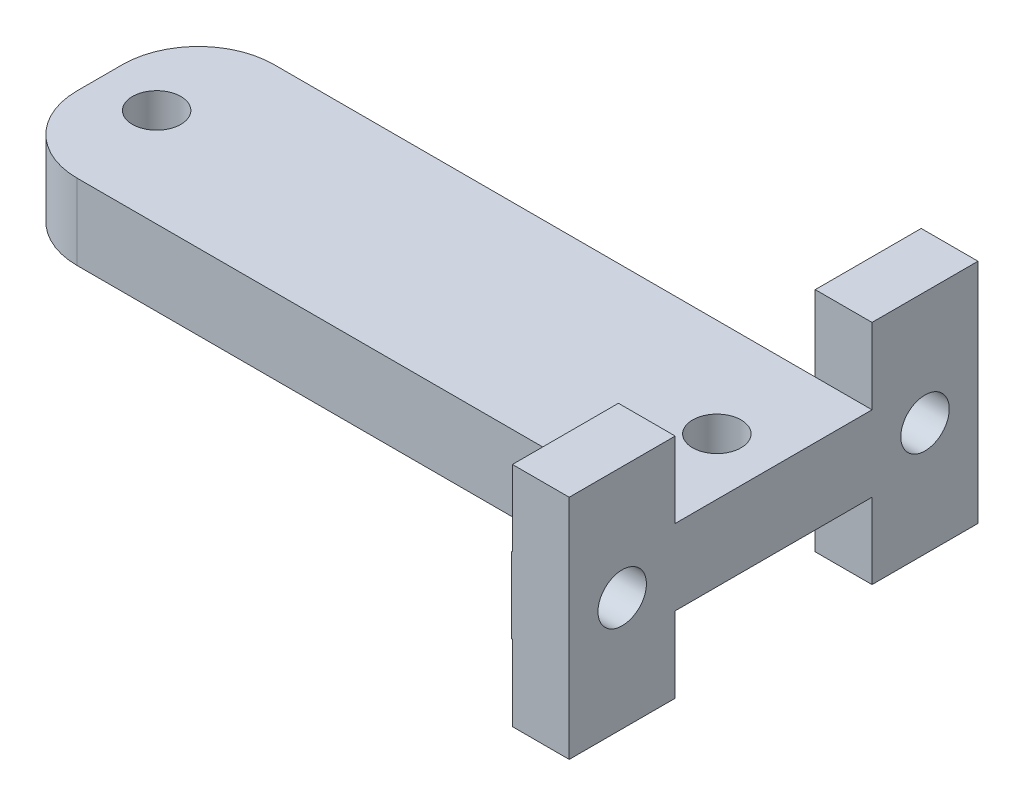
SolidWorks part; units mm, degrees
ref_plane "前视基准面" through (0, 0, 0) normal (0, 0, 1) x (1, 0, 0)
ref_plane "上视基准面" through (0, 0, 0) normal (0, 1, 0) x (1, 0, 0)
ref_plane "右视基准面" through (0, 0, 0) normal (1, 0, 0) x (0, 0, -1)
sketch "草图1" plane through (0, 0, 0) normal (0, 1, 0) x (1, 0, 0)
  line L0 (0, 0) -> (0, -100)
  line L1 (0, 0) -> (100, 0)
  line L2 (100, 0) -> (100, -100)
  line L3 (100, -100) -> (0, -100)
  dimension "D1" = 100
extrude "凸台-拉伸1" add sketch "草图1" along normal blind 10
sketch "草图2" plane through (0, 10, 0) normal (0, 1, 0) x (1, 0, 0)
  line L0 (20.6546, -10.25) -> (20.6546, -13)
  line L1 (20.6546, -13) -> (50.1546, -13)
  line L2 (50.1546, -13) -> (50.1546, -10.25)
  line L3 (50.1546, -10.25) -> (53.9046, -10.25)
  line L4 (16.9046, -2.75) -> (20.6546, -2.75)
  line L5 (20.6546, -2.75) -> (20.6546, 0)
  line L6 (100, 0) -> (0, 0) construction
  line L7 (20.6546, 0) -> (20.6546, -2.75) construction
  line L8 (20.6546, 0) -> (50, 0)
  line L9 (50, 0) -> (50.1546, -2.75)
  line L10 (50.1546, -2.75) -> (53.9046, -2.75)
  line L11 (16.9046, -10.25) -> (20.6546, -10.25)
  line L12 (20.6546, 0) -> (0, 0)
  line L13 (0, 0) -> (0, -100)
  line L14 (0, -100) -> (100, -100)
  line L15 (100, -100) -> (100, 0)
  line L16 (100, 0) -> (50, 0)
  line L17 (20.6546, -13) -> (0, -13)
  line L18 (50.1546, -13) -> (100, -13)
  line L19 (100, -13) -> (100, -100)
  arc A0 (53.9046, -10.25) -> (53.9046, -2.75) centre (53.9046, -6.5) ccw
  arc A1 (16.9046, -2.75) -> (16.9046, -10.25) centre (16.9046, -6.5) ccw
  line M3 (0, -100) -> (100, -100)
  line M4 (100, -100) -> (100, 0)
extrude "切除-拉伸3" cut sketch "草图2" against normal blind 27 contours L18 L1 L17 L13 M3 M4
sketch "草图4" plane through (0, 10, 0) normal (0, 1, 0) x (1, 0, 0)
  line L0 (16.9046, -6.5) -> (13.1546, -6.5)
  line L1 (13.1546, -6.5) -> (13.1546, 0)
  line L2 (100, 0) -> (0, 0) construction
  line L3 (13.1546, 0) -> (13.1546, -13)
  line L4 (0, -13) -> (100, -13) construction
  line L5 (53.9046, -6.5) -> (57.6546, -6.5)
  line L6 (57.6546, -6.5) -> (57.6546, -13)
  line L7 (57.6546, -13) -> (57.6546, 0)
  line L8 (57.6546, 0) -> (100, 0)
  line L9 (100, 0) -> (100, -13)
  line L10 (100, -13) -> (57.6546, -13)
  line L11 (13.1546, -13) -> (0, -13)
  line L12 (0, -13) -> (0, 0)
  line L13 (0, 0) -> (13.1546, 0)
  arc A0 (16.9046, -2.75) -> (16.9046, -10.25) centre (16.9046, -6.5) ccw construction
  arc A1 (53.9046, -10.25) -> (53.9046, -2.75) centre (53.9046, -6.5) ccw construction
  line M1 (0, -13) -> (100, -13)
  line M2 (100, -13) -> (100, 0)
  line M3 (100, 0) -> (0, 0)
  line M4 (0, 0) -> (0, -13)
extrude "切除-拉伸4" cut sketch "草图4" against normal blind 27 contours L3 L1 M3 M4 M1 | L7 L6 M1 M2 M3
sketch "草图5" plane through (0, 10, 0) normal (0, 1, 0) x (1, 0, 0)
  circle A0 centre (16.9046, -6.5) radius 1.6
  circle A1 centre (53.9046, -6.5) radius 1.6
extrude "切除-拉伸5" cut sketch "草图5" against normal blind 27
sketch "草图6" plane through (0, 0, 13) normal (0, 0, 1) x (1, 0, 0)
  line L0 (50.1546, 10) -> (50.1546, 0)
  line L1 (13.1546, 10) -> (57.6546, 10) construction
  line L2 (50.1546, 17.2) -> (50.1546, 10) construction
  line L3 (57.6546, 0) -> (13.1546, 0) construction
  line L4 (50.1546, 5) -> (13.1546, 5)
  line L5 (13.1546, 10) -> (13.1546, 0) construction
  line L6 (13.1546, 5) -> (13.1546, 0)
  line L7 (13.1546, 0) -> (50.1546, 0)
  line L8 (50.1546, 5) -> (57.6546, 5)
  line L9 (57.6546, 0) -> (57.6546, 10) construction
  line L10 (57.6546, 5) -> (57.6546, 0)
  line L11 (57.6546, 0) -> (50.1546, 0)
  line M2 (13.1546, 10) -> (13.1546, 0)
  line M3 (13.1546, 0) -> (57.6546, 0)
  line M4 (57.6546, 0) -> (57.6546, 10)
extrude "切除-拉伸6" cut sketch "草图6" against normal blind 27 contours L0 L4 M2 M3 | L8 L0 M3 M4
sketch "草图7" plane through (0, 10, 0) normal (0, 1, 0) x (1, 0, 0)
  line L0 (53.9046, -6.5) -> (53.9046, -13)
  line L1 (13.1546, -13) -> (57.6546, -13) construction
sketch "草图8" plane through (0, 0, 13) normal (0, 0, 1) x (1, 0, 0)
  line L0 (53.8487, 10) -> (53.8487, 5)
  line L1 (13.1546, 10) -> (57.6546, 10) construction
  line L2 (57.6546, 5) -> (13.1546, 5) construction
  line L3 (53.8487, 5) -> (57.6546, 5)
  line L4 (57.6546, 5) -> (57.6546, 10)
  line L5 (57.6546, 10) -> (53.8487, 10)
extrude "凸台-拉伸2" add sketch "草图8" along normal blind 7
sketch "草图9" plane through (0, 10, 0) normal (0, 1, 0) x (1, 0, 0)
  line L0 (53.9046, -6.5) -> (53.9046, 0)
  line L1 (57.6546, 0) -> (13.1546, 0) construction
sketch "草图10" plane through (0, 0, 0) normal (0, 0, -1) x (-1, 0, 0)
  line L0 (-53.9046, 10) -> (-53.9046, 5)
  line L1 (-57.6546, 5) -> (-13.1546, 5) construction
  line L2 (-53.9046, 5) -> (-57.6546, 5)
  line L3 (-57.6546, 5) -> (-57.6546, 10)
  line L4 (-57.6546, 10) -> (-53.9046, 10)
extrude "凸台-拉伸3" add sketch "草图10" along normal blind 7
sketch "草图11" plane through (13.1546, 0, 0) normal (-1, 0, 0) x (0, 0, 1)
  line L0 (6.5, 10) -> (6.5, 5)
  line L1 (6.5, 10) -> (13, 10) construction
  line L2 (6.5, 10) -> (0, 10) construction
  line L3 (0, 5) -> (13, 5) construction
fillet "圆角1" radius 5 1 edges at (13.1546, 7.5, 0)
fillet "圆角2" radius 5 1 edges at (13.1546, 7.5, 13)
sketch "草图14" plane through (57.6546, 0, 0) normal (1, 0, 0) x (0, 0, -1)
  line L0 (-13, 10) -> (-20, 10)
  line L1 (-20, 10) -> (-20, 15)
  line L2 (-20, 15) -> (-13, 15)
  line L3 (-13, 15) -> (-13, 10)
  line L4 (-20, 5) -> (-20, 0)
  line L5 (-20, 0) -> (-13, 0)
  line L6 (-13, 0) -> (-13, 5)
  line L7 (-13, 5) -> (-20, 5)
  line L8 (0, 10) -> (0, 15)
  line L9 (0, 10) -> (7, 10)
  line L10 (7, 10) -> (7, 15)
  line L11 (7, 15) -> (0, 15)
  line L12 (0, 5) -> (7, 5)
  line L13 (7, 5) -> (7, 0)
  line L14 (7, 0) -> (0, 0)
  line L15 (0, 0) -> (0, 5)
extrude "凸台-拉伸6" add sketch "草图14" against normal up to vertex (3.75 mm away) up to point (53.9046, 10, -7)
sketch "草图15" plane through (53.8487, 0, 0) normal (-1, 0, 0) x (0, 0, 1)
  line L0 (13, 10) -> (20, 5)
  line L1 (6.5, 10) -> (13, 10) construction
  line L2 (13, 10) -> (13, 5) construction
  line L3 (0, 10) -> (0, 5)
  line L4 (0, 5) -> (-7, 5)
  line L5 (-7, 0) -> (-7, 15) construction
  line L6 (-7, 5) -> (-7, 10)
  line L7 (-7, 10) -> (0, 10)
  line L8 (-7, 5) -> (0, 10)
  circle A0 centre (16.5, 7.5) radius 1.6
  circle A1 centre (-3.5, 7.5) radius 1.6
extrude "切除-拉伸8" cut sketch "草图15" against normal up to vertex contours L8 A1 | L8 A1 | L0 A0 | L0 A0
